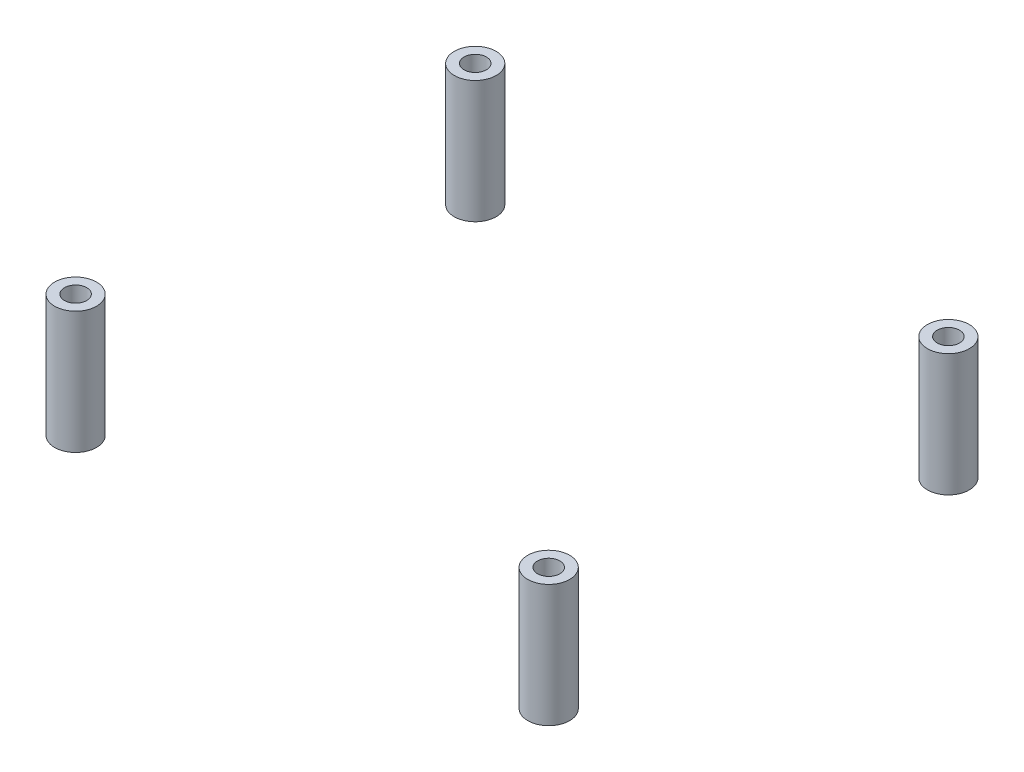
SolidWorks part; units mm, degrees
ref_plane "Front Plane" through (0, 0, 0) normal (0, 0, 1) x (1, 0, 0)
ref_plane "Top Plane" through (0, 0, 0) normal (0, 1, 0) x (1, 0, 0)
ref_plane "Right Plane" through (0, 0, 0) normal (1, 0, 0) x (0, 0, -1)
sketch "Sketch2" plane through (0, 0, 0) normal (0, 1, 0) x (1, 0, 0)
  circle A0 centre (128.4552, 5.4768) radius 1.3682
  circle A1 centre (186.4527, 5.47) radius 2.5682
  circle A2 centre (186.4527, 5.47) radius 1.3682
  circle A3 centre (186.4527, 54.4603) radius 1.3682
  circle A4 centre (128.455, 54.4603) radius 1.3682
  circle A5 centre (128.4552, 5.4768) radius 2.5682
  circle A6 centre (186.4527, 54.4603) radius 2.5682
  circle A7 centre (128.455, 54.4603) radius 2.5682
  point P14 (185.0845, 5.47)
  point P16 (186.4527, 55.8284)
  point P18 (129.8232, 54.4603)
  dimension "D1" = 1.2
extrude "Boss-Extrude1" add sketch "Sketch2" along normal blind 15
